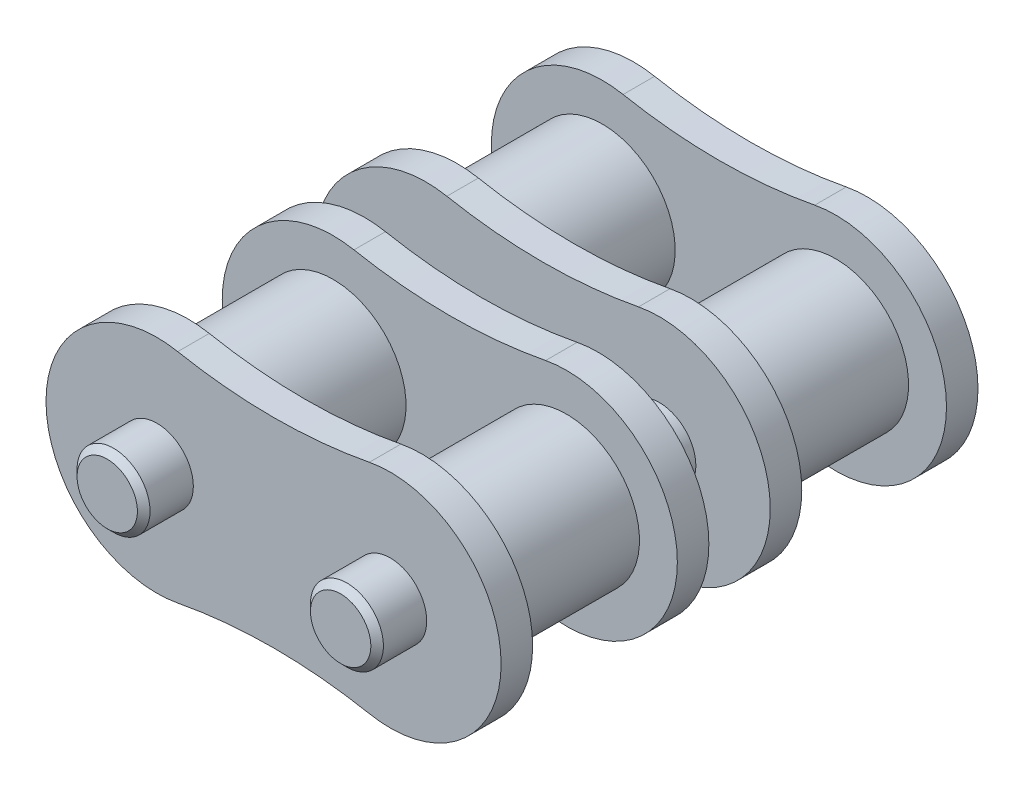
SolidWorks part; units mm, degrees
ref_plane "前视基准面" through (0, 0, 0) normal (0, 0, 1) x (1, 0, 0)
ref_plane "上视基准面" through (0, 0, 0) normal (0, 1, 0) x (1, 0, 0)
ref_plane "右视基准面" through (0, 0, 0) normal (1, 0, 0) x (0, 0, -1)
sketch "草图1" plane through (0, 0, 0) normal (0, 0, 1) x (1, 0, 0)
  line L0 (-12.7, 0) -> (12.7, 0) construction
  line L1 (0, 10.8585) -> (0, -10.8585) construction
  line L2 (12.7, 0) -> (35.31, 0) construction
  line L3 (35.31, 0) -> (51.06, 0) construction
  circle A0 centre (-12.7, 0) radius 12.065
  circle A1 centre (12.7, 0) radius 12.065
  circle A2 centre (0, 66.2389) radius 55.3804
  circle A3 centre (0, -66.2389) radius 55.3804
  circle A4 centre (-12.7, 0) radius 7.94
  circle A5 centre (12.7, 0) radius 7.94
  circle A6 centre (-12.7, 0) radius 3.97
  circle A7 centre (12.7, 0) radius 3.97
  point P16 (75.4, 0)
  point P18 (41.99, 0)
  point P19 (14.7, 0)
  dimension "h2" = 24.13
  dimension "d1" = 15.88
  dimension "d2" = 7.94
  dimension "p" = 25.4
  dimension "h3" = 21.717
  dimension "b2" = 22.61
  dimension "b1" = 15.75
  dimension "b5" = 62.7
  dimension "P1" = 29.29
  dimension "z" = 2
sketch "草图2" plane through (0, 0, 0) normal (0, 0, 1) x (1, 0, 0)
  circle A0 centre (12.7, 0) radius 7.94 construction
  circle A1 centre (-12.7, 0) radius 7.94 construction
  circle A2 centre (12.7, 0) radius 7.94
  circle A3 centre (-12.7, 0) radius 7.94
extrude "拉伸1" add sketch "草图2" along normal mid plane 15.75
sketch "草图3" plane through (0, 0, 7.875) normal (0, 0, 1) x (1, 0, 0)
  circle A0 centre (-12.7, 0) radius 12.065 construction
  arc A1 (-10.4282, 11.8492) -> (-10.4282, -11.8492) centre (-12.7, 0) ccw
  circle A2 centre (12.7, 0) radius 12.065 construction
  arc A3 (10.4282, -11.8492) -> (10.4282, 11.8492) centre (12.7, 0) ccw
  circle A4 centre (0, 66.2389) radius 55.3804 construction
  arc A5 (-10.4282, 11.8492) -> (10.4282, 11.8492) centre (0, 66.2389) ccw
  circle A6 centre (0, -66.2389) radius 55.3804 construction
  arc A7 (10.4282, -11.8492) -> (-10.4282, -11.8492) centre (0, -66.2389) ccw
extrude "拉伸2" add sketch "草图3" along normal blind 3.43
mirror "镜向1" about plane through (0, 0, 0) normal (0, 0, 1) of "拉伸2"
sketch "草图5" plane through (0, 0, 0) normal (0, 0, 1) x (1, 0, 0)
  line L0 (12.7, 0) -> (37.302, -6.3167) construction
  line L1 (-12.7, 0) -> (12.7, 0) construction
  line L2 (-12.7, 0) -> (-776.8532, -96.535)
  line L4 (0, -100.5309) -> (-768.1907, -165.1058) construction
  line L5 (37.302, -6.3167) -> (59.5602, -18.5533) construction
  arc A0 (30.9597, -197.0153) -> (-12.7, 0) centre (0, -100.5309) ccw
  arc A1 (-776.8532, -96.535) -> (-783.5035, -232.504) centre (-768.1907, -165.1058) ccw
  arc A2 (-783.5035, -232.504) -> (30.9597, -197.0153) centre (-441.1553, 1274.3085) ccw
  dimension "R2" = 202.6597
  dimension "R1" = 138.2317
  dimension "a" = 770.9
  dimension "La" = 770.2266
  dimension "L2" = 299.6078
  dimension "L" = 825
  dimension "L1" = 193.0074
curve "组合曲线1"
pattern_linear "阵列(线性)1" count 2 spacing 29.29 along (0, 0, 1) of bodies 105 123 124
sketch "草图4" plane through (0, 0, 0) normal (0, 0, 1) x (1, 0, 0)
  circle A0 centre (12.7, 0) radius 3.97 construction
  circle A1 centre (-12.7, 0) radius 3.97 construction
  circle A2 centre (12.7, 0) radius 3.97
  circle A3 centre (-12.7, 0) radius 3.97
extrude "拉伸3" add sketch "草图4" against normal blind 16.705 and the other way blind 45.995
chamfer "倒角1" distance 0.686 angle 45 4 edges at (16.67, 0, -16.705) (-8.73, 0, -16.705) (16.67, 0, 45.995) (-8.73, 0, 45.995)
equation "\"D1@拉伸1\" = \"b1@草图1\""
equation "\"D1@拉伸2\" = (  \"b2@草图1\" - \"D1@拉伸1\" )  / 2"
equation "\"D1@拉伸3\" = (\"b5@草图1\"-(\"z@草图1\"-1)*\"P1@草图1\")/2"
equation "\"D2@拉伸3\"= \"b5@草图1\"-\"D1@拉伸3\""
equation "\"D1@倒角1\" = \"D1@拉伸2\" / 5"
equation "\"h3@草图1\" = \"h2@草图1\" * 0.9"
equation "\"D3@阵列(线性)1\" = \"P1@草图1\""
equation "\"D1@阵列(线性)1\" =\"z@草图1\""
